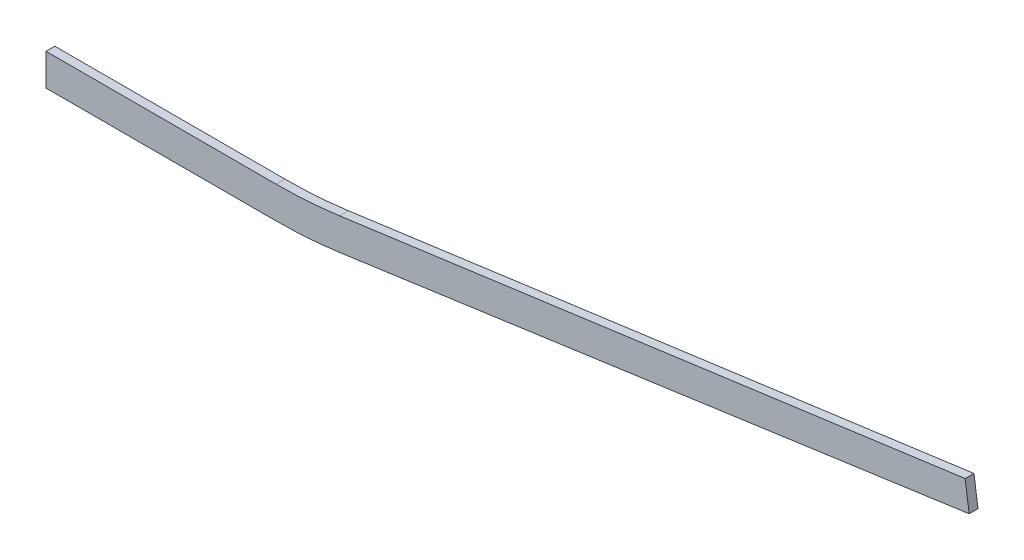
SolidWorks part; units mm, degrees
ref_plane "Front Plane" through (0, 0, 0) normal (0, 0, 1) x (1, 0, 0)
ref_plane "Top Plane" through (0, 0, 0) normal (0, 1, 0) x (1, 0, 0)
ref_plane "Right Plane" through (0, 0, 0) normal (1, 0, 0) x (0, 0, -1)
sketch "Sketch1" plane through (0, 0, 0) normal (0, 0, 1) x (1, 0, 0)
  line L0 (3698.4478, 2129.4435) -> (3698.4478, 2163.8333)
  line L1 (3698.4478, 2129.4435) -> (3945.5, 2129.4435)
  line L2 (3698.4478, 2163.8333) -> (3946.5584, 2163.8333)
  line L3 (4016.1999, 2134.3873) -> (4694.3978, 2229.7018)
  line L4 (4015.1713, 2168.4882) -> (4690.0713, 2260.4864)
  line L5 (4694.3978, 2229.7018) -> (4690.0713, 2260.4864)
  arc A0 (3945.5, 2129.4435) -> (4016.1999, 2134.3873) centre (3945.5, 2637.4435) ccw
  arc A1 (3946.5584, 2163.8333) -> (4015.1713, 2168.4882) centre (3946.5584, 2671.8333) ccw
extrude "Boss-Extrude1" add sketch "Sketch1" along normal blind 9.525
